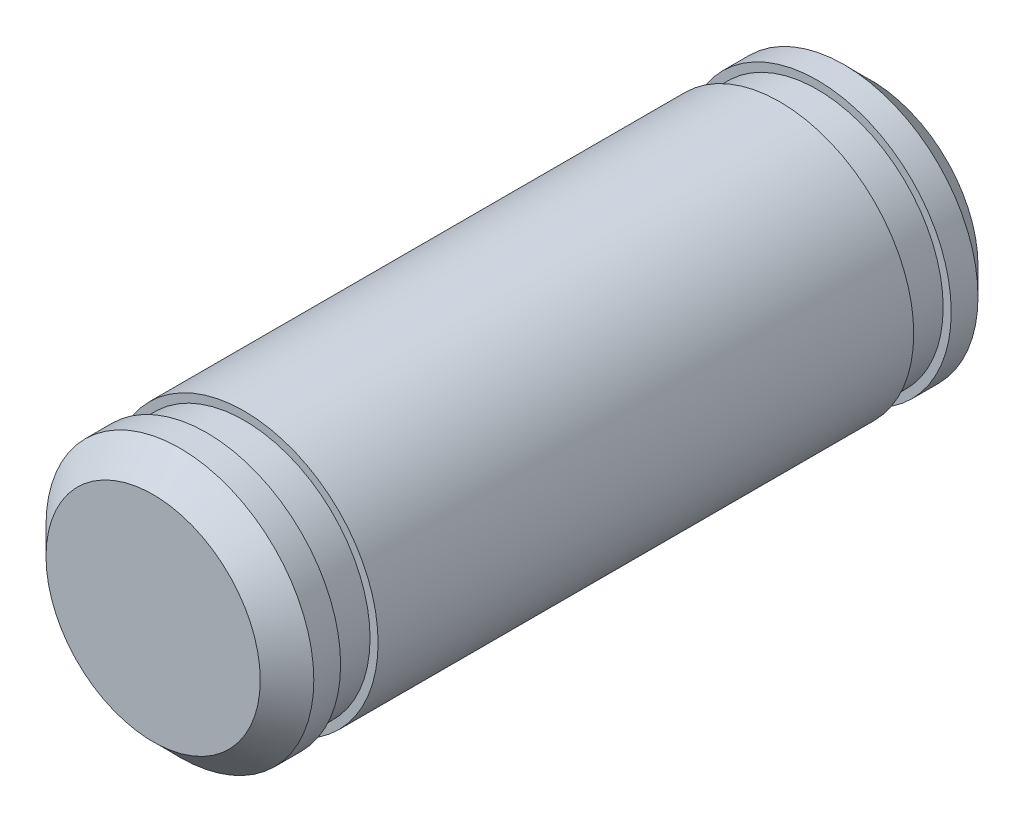
SolidWorks part; units mm, degrees
material "Chromowa stal nierdzewna"
ref_plane "Płaszczyzna przednia" through (0, 0, 0) normal (0, 0, 1) x (1, 0, 0)
ref_plane "Płaszczyzna górna" through (0, 0, 0) normal (0, 1, 0) x (1, 0, 0)
ref_plane "Płaszczyzna prawa" through (0, 0, 0) normal (1, 0, 0) x (0, 0, -1)
sketch "Szkic1" plane through (0, 0, 0) normal (0, 0, 1) x (1, 0, 0)
  circle A0 centre (0, 0) radius 2.5
  dimension "D1" = 5
extrude "Dodanie-wyciągnięcie1" add sketch "Szkic1" along normal blind 13.4
chamfer "Sfazowanie1" distance 0.5 angle 45 2 edges at (2.5, 0, 0) (2.5, 0, 13.4)
sketch "Szkic2" plane through (0, 0, 13.4) normal (0, 0, 1) x (1, 0, 0)
  circle A0 centre (0, 0) radius 2.5
  circle A1 centre (0, 0) radius 2.35
  dimension "D1" = 5
  dimension "D2" = 4.7
extrude "Wytnij-wyciągnięcie1" cut sketch "Szkic2" against normal blind 0.7 from offset 1 offset against normal yes
sketch "Szkic3" plane through (0, 0, 0) normal (0, 0, -1) x (-1, 0, 0)
  circle A0 centre (0, 0) radius 2.5
  circle A1 centre (0, 0) radius 2.35
  dimension "D1" = 4.7
  dimension "D2" = 5
extrude "Wytnij-wyciągnięcie2" cut sketch "Szkic3" against normal blind 0.7 from offset 1 offset against normal yes
